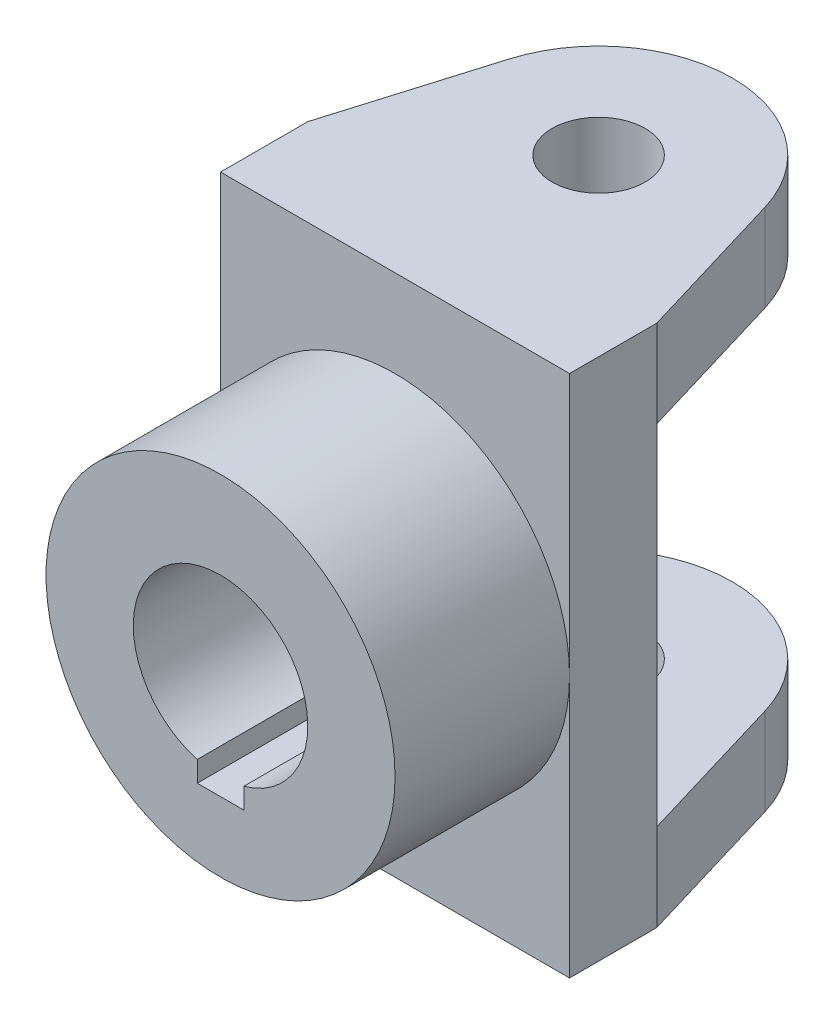
SolidWorks part; units mm, degrees
ref_plane "Front Plane" through (0, 0, 0) normal (0, 0, 1) x (1, 0, 0)
ref_plane "Top Plane" through (0, 0, 0) normal (0, 1, 0) x (1, 0, 0)
ref_plane "Right Plane" through (0, 0, 0) normal (1, 0, 0) x (0, 0, -1)
sketch "Sketch1" plane through (0, 0, 0) normal (0, 0, 1) x (1, 0, 0)
  line L1 (30, -45) -> (-30, -45)
  line L2 (30, -45) -> (30, 45)
  line L3 (30, 45) -> (-30, 45)
  line L4 (-30, -45) -> (-30, 45)
  line L5 (30, -45) -> (-30, 45) construction
  line L6 (30, 45) -> (-30, -45) construction
  point P0 (0, 0)
  dimension "D1" = 60
  dimension "D2" = 90
extrude "Boss-Extrude2" add sketch "Sketch1" along normal blind 15
sketch "Sketch2" plane through (0, 0, 15) normal (0, 0, 1) x (1, 0, 0)
  line L0 (-4, -14.4568) -> (-4, -18)
  line L3 (-4, -18) -> (4, -18)
  line L4 (4, -14.4568) -> (4, -18)
  arc A0 (4, -14.4568) -> (-4, -14.4568) centre (0, 0) ccw
  circle A1 centre (0, 0) radius 30
  dimension "D1" = 30
  dimension "D2" = 60
extrude "Boss-Extrude4" add sketch "Sketch2" along normal blind 30 contours A0 L0 L3 L4
sketch "Sketch3" plane through (0, 45, 0) normal (0, 1, 0) x (1, 0, 0)
  line L0 (30, -15) -> (-30, -15) construction
  line L1 (30, 0) -> (22.0329, 26.5993)
  line L2 (30, 0) -> (-30, 0)
  line L3 (-30, 0) -> (-22.0329, 26.5993)
  circle A0 centre (0, 20) radius 8
  arc A1 (-11.3578, 0) -> (11.3578, 0) centre (0, 20) ccw
  arc A2 (22.0329, 26.5993) -> (-22.0329, 26.5993) centre (0, 20) ccw
  line M7 (30, 0) -> (-30, 0)
  dimension "D1" = 16
  dimension "D2" = 46
  dimension "D3" = 35
extrude "Boss-Extrude5" add sketch "Sketch3" against normal blind 15 contours L1 A2 L3 L2 A0 M7
mirror "Mirror1" about plane through (0, 0, 0) normal (0, 1, 0) of "Boss-Extrude5"
